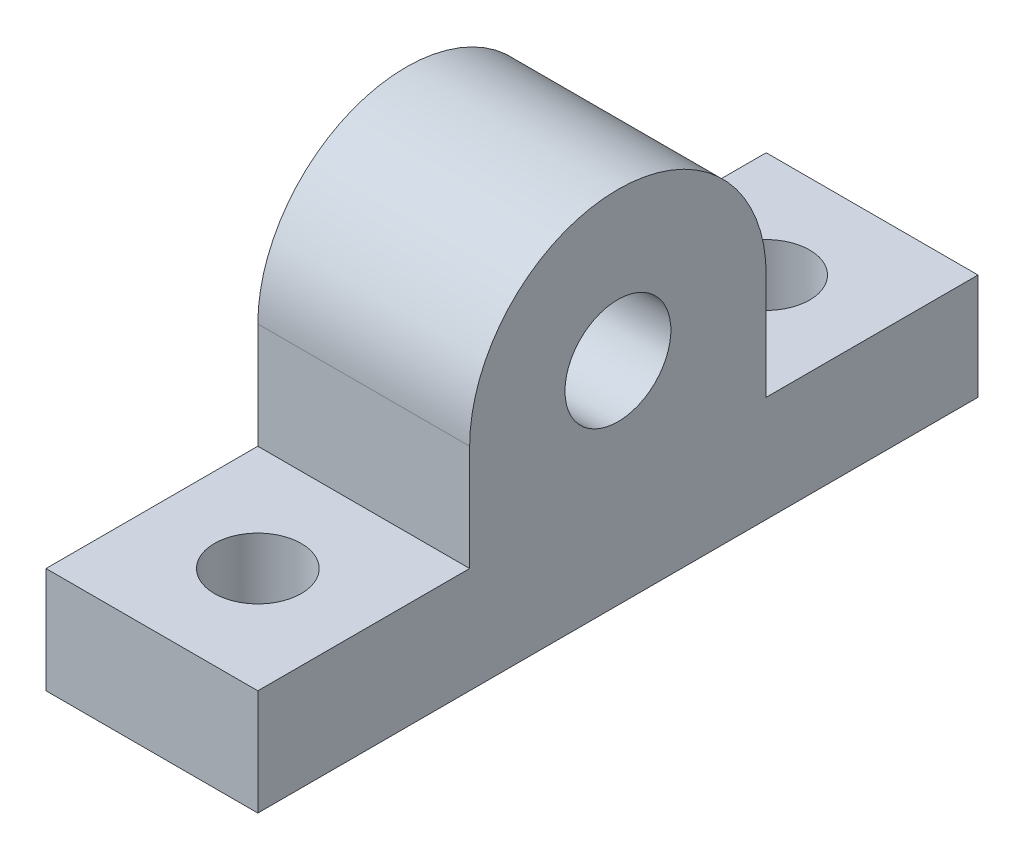
SolidWorks part; units mm, degrees
ref_plane "Plan de face" through (0, 0, 0) normal (0, 0, 1) x (1, 0, 0)
ref_plane "Plan de dessus" through (0, 0, 0) normal (0, 1, 0) x (1, 0, 0)
ref_plane "Plan de droite" through (0, 0, 0) normal (1, 0, 0) x (0, 0, -1)
sketch "Esquisse1" plane through (0, 0, 0) normal (1, 0, 0) x (0, 0, -1)
  line L0 (-32.1429, 0) -> (37.0408, 0) construction
  line L1 (0, 22.7041) -> (0, -22.2959) construction
  line L2 (17, 0) -> (-17, 0)
  line L3 (-17, 0) -> (-17, 5)
  line L4 (-17, 5) -> (-7, 5)
  line L5 (-7, 5) -> (-7, 10)
  line L6 (-8.5714, 10) -> (21.8367, 10) construction
  line L7 (7, 5) -> (7, 10)
  line L8 (17, 5) -> (7, 5)
  line L9 (17, 0) -> (17, 5)
  arc A0 (-7, 10) -> (7, 10) centre (0, 10) cw
  circle A1 centre (0, 10) radius 2.5
  point P18 (0, 0)
  dimension "D1" = 5
  dimension "D3" = 2.5
  dimension "D2" = 10
  dimension "D4" = 7
  dimension "D5" = 10
extrude "Boss.-Extru.1" add sketch "Esquisse1" along normal blind 10
sketch "Esquisse2" plane through (0, 5, 0) normal (0, 1, 0) x (1, 0, 0)
  line L0 (5, -17) -> (5, 17) construction
  line L1 (10, 17) -> (0, 17) construction
  line L2 (0, -12) -> (10, -12) construction
  line L3 (0, 12) -> (10, 12) construction
  line L4 (0, -7) -> (0, -17)
  line L5 (0, -17) -> (10, -17)
  line L6 (10, -17) -> (10, -7)
  line L7 (10, -7) -> (0, -7)
  line L8 (0, -7) -> (0, -17)
  line L9 (0, -17) -> (10, -17)
  line L10 (10, -17) -> (10, -7)
  line L11 (10, -7) -> (0, -7)
  line L15 (0, 17) -> (0, 7)
  line L16 (0, 7) -> (10, 7)
  line L17 (10, 7) -> (10, 17)
  line L18 (10, 17) -> (0, 17)
  line L19 (0, 17) -> (0, 7)
  line L20 (0, 7) -> (10, 7)
  line L21 (10, 7) -> (10, 17)
  line L22 (10, 17) -> (0, 17)
  circle A0 centre (5, 12) radius 2.05
  circle A1 centre (5, -12) radius 2.05
  dimension "D3" = 4.1
  dimension "D4" = 4.1
  dimension "D2" = 0
  dimension "D1" = 0
extrude "Enlèv. mat.-Extru.1" cut sketch "Esquisse2" against normal through all both and the other way through all contours A1 | A0
